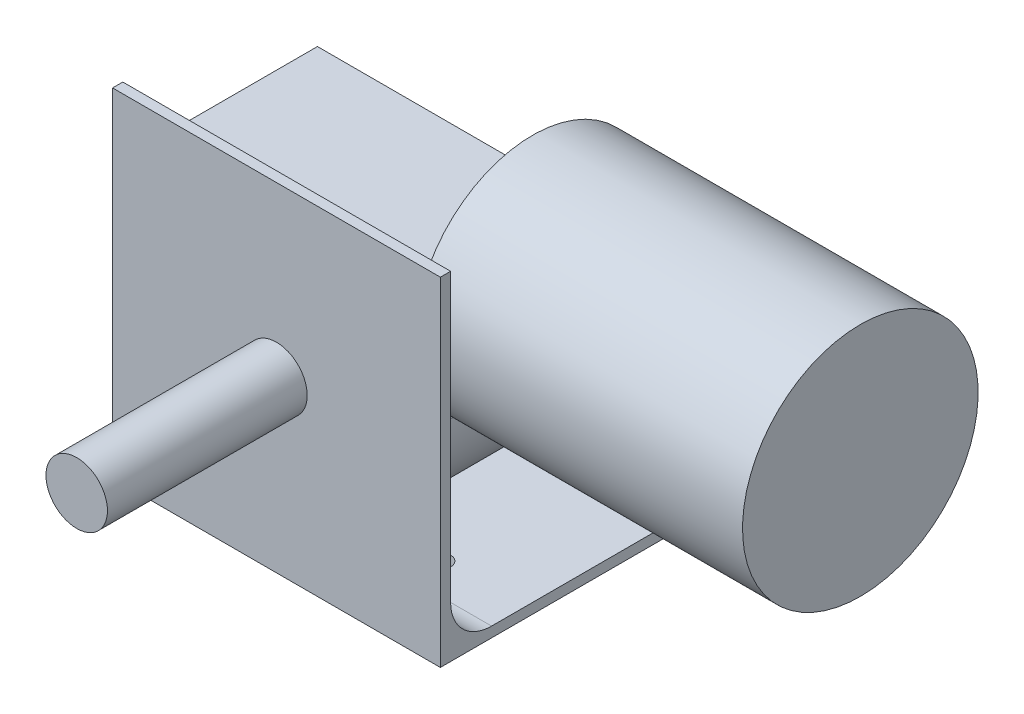
SolidWorks part; units mm, degrees
material "Cast Alloy Steel"
ref_plane "Front Plane" through (0, 0, 0) normal (0, 0, 1) x (1, 0, 0)
ref_plane "Top Plane" through (0, 0, 0) normal (0, 1, 0) x (1, 0, 0)
ref_plane "Right Plane" through (0, 0, 0) normal (1, 0, 0) x (0, 0, -1)
sketch "Sketch1" plane through (0, 0, 0) normal (0, 1, 0) x (1, 0, 0)
  line L0 (-50.8, 50.8) -> (50.8, -50.8) construction
  line L1 (-50.8, 50.8) -> (50.8, 50.8)
  line L2 (-50.8, 50.8) -> (-50.8, -50.8)
  line L3 (-50.8, -50.8) -> (50.8, -50.8)
  line L4 (50.8, 50.8) -> (50.8, -50.8)
  point P4 (0, 0)
  dimension "D1" = 101.6
  dimension "D2" = 101.6
extrude "Extrude1" add sketch "Sketch1" along normal blind 3.175
sketch "Sketch2" plane through (0, 3.175, 0) normal (0, 1, 0) x (1, 0, 0)
  line L0 (50.8, -50.8) -> (50.8, 50.8) construction
  line L1 (-50.8, -50.8) -> (50.8, -50.8)
  line L2 (-50.8, -50.8) -> (-50.8, -47.625)
  line L3 (-50.8, -47.625) -> (50.8, -47.625)
  line L4 (50.8, -50.8) -> (50.8, -47.625)
  dimension "D1" = 3.175
extrude "Extrude2" add sketch "Sketch2" along normal blind 101.6
fillet "Fillet1" radius 12.7 1 edges
sketch "Sketch3" plane through (0, 0, 50.8) normal (0, 0, 1) x (1, 0, 0)
  line L0 (-50.8, 104.775) -> (50.8, 0) construction
  circle A0 centre (0, 52.3875) radius 9.525
  dimension "D1" = 19.05
extrude "Extrude3" add sketch "Sketch3" along normal blind 61.9125
hole_wizard "#97 (0.0059) Diameter Hole1" positions "Sketch5" profile "Sketch6" hole size "#97" standard "Ansi Inch" end condition through all
sketch "Sketch5" plane through (0, 3.175, 0) normal (0, 1, 0) x (-1, 0, 0)
  line L0 (-25.4, 25.4) -> (25.4, 25.4) construction
  line L1 (25.4, 25.4) -> (25.4, -25.4) construction
  line L2 (25.4, -25.4) -> (-25.4, -25.4) construction
  line L3 (-25.4, -25.4) -> (-25.4, 25.4) construction
  line L5 (-50.8, 34.925) -> (-50.8, -50.8) construction
  line L6 (50.8, -50.8) -> (50.8, 34.925) construction
  line L7 (-50.8, -50.8) -> (50.8, -50.8) construction
  line L8 (50.8, 50.8) -> (-50.8, 50.8) construction
  point P0 (-25.4, 25.4)
  point P1 (25.4, 25.4)
  point P3 (25.4, -25.4)
  point P5 (-25.4, -25.4)
  dimension "D1" = 25.4
  dimension "D2" = 25.4
  dimension "D3" = 25.4
  dimension "D4" = 25.4
sketch "Sketch6" plane through (25.4, 3.175, 25.4) normal (1, 0, 0) x (0, 0, 1)
  line L0 (0, 0) -> (0, 3.175)
  line L1 (0, 3.175) -> (3.175, 3.175)
  line L2 (3.175, 3.175) -> (3.175, 0)
  line L5 (3.175, 0) -> (0, 0)
  line L11 (0, -6.35) -> (0, 107.95) construction
  dimension "Thru Hole Dia." = 6.35
  dimension "Thru Hole Depth" = 3.175
sketch "Sketch7" plane through (0, 0, 47.625) normal (0, 0, -1) x (-1, 0, 0)
  line L0 (-50.8, 104.775) -> (50.8, 0) construction
  line L2 (-38.1, 52.3875) -> (38.1, 52.3875)
  line L3 (-38.1, 52.3875) -> (-38.1, 96.8375)
  line L4 (-38.1, 96.8375) -> (38.1, 96.8375)
  line L5 (38.1, 52.3875) -> (38.1, 96.8375)
  circle A0 centre (0, 52.3875) radius 38.1
  line M2 (-50.8, 15.875) -> (50.8, 15.875)
  dimension "D1" = 76.2
  dimension "D2" = 44.45
extrude "Extrude4" add sketch "Sketch7" along normal blind 47.625 contours L0 L2 A0 M2 | L2 L0 A0 | A0 L0 L2 | L0 A0 L2 | A0 M2
sketch "Sketch10" plane through (38.1, 0, 0) normal (1, 0, 0) x (0, 0, -1)
  line L0 (-34.925, 3.175) -> (50.8, 3.175) construction
  line L1 (-47.625, 52.3875) -> (-47.625, 96.8375) construction
  circle A0 centre (-9.525, 79.375) radius 36.5125
  dimension "D1" = 73.025
  dimension "D2" = 76.2
  dimension "D3" = 38.1
extrude "Extrude12" add sketch "Sketch10" along normal blind 101.6
